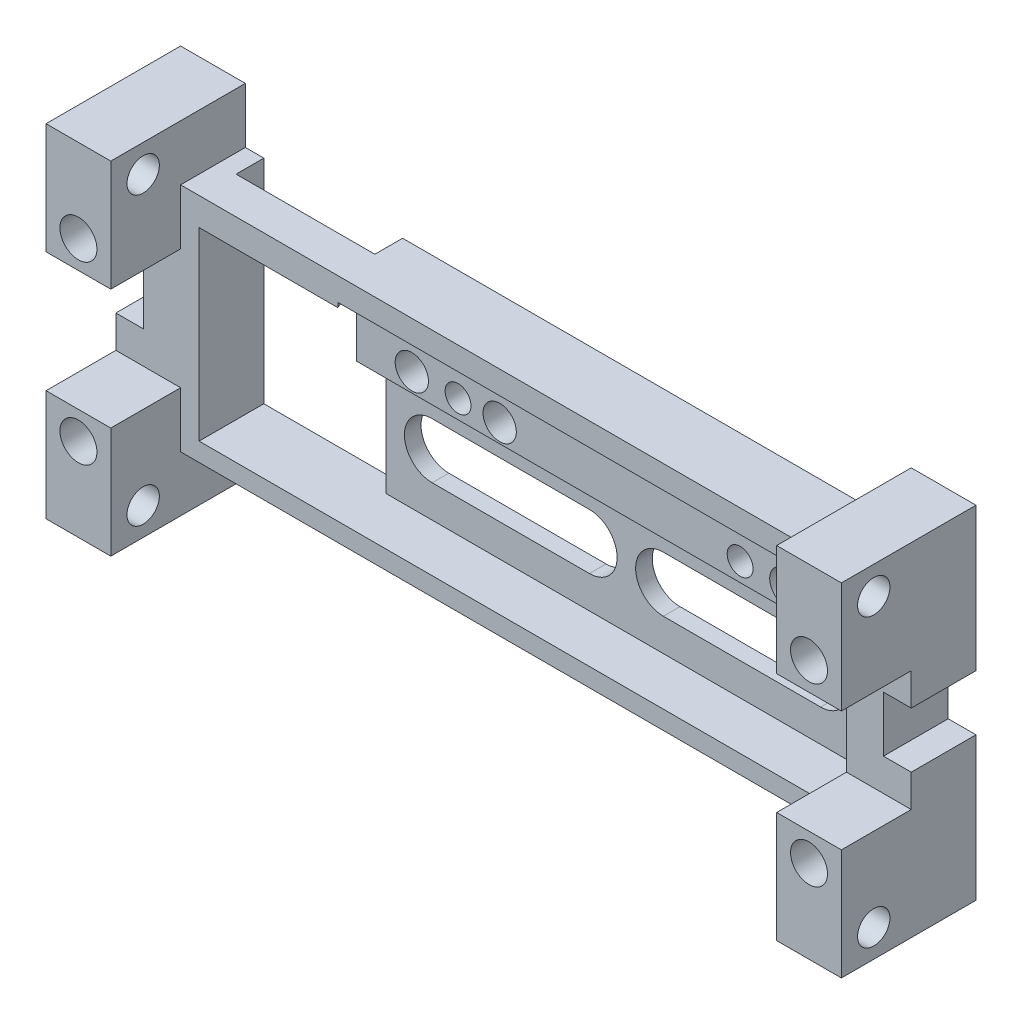
SolidWorks part; units mm, degrees
other "标注1"
sketch "草图15" plane through (0, -6, 0) normal (-0.9712, -0.0025, -0.2382) x (-0.2378, 0.0659, 0.9691)
other "标注2"
sketch "草图16" plane through (0, 31, 0) normal (-0.9763, 0.0726, -0.2038) x (-0.196, 0.1022, 0.9753)
other "标注3"
sketch "草图18" plane through (86, -6, 14) normal (0.0371, -0.0622, 0.9974) x (0.9993, -0.0087, -0.0377)
ref_plane "前视基准面" through (0, 0, 0) normal (0, 0, 1) x (1, 0, 0)
ref_plane "上视基准面" through (0, 0, 0) normal (0, 1, 0) x (1, 0, 0)
ref_plane "右视基准面" through (0, 0, 0) normal (1, 0, 0) x (0, 0, -1)
other "Configuration Table"
sketch "草图1" plane through (0, 0, 0) normal (0, 0, 1) x (1, 0, 0)
  line L1 (0, 0) -> (86, 0)
  line L2 (0, 0) -> (0, 25)
  line L3 (0, 25) -> (86, 25)
  line L4 (86, 0) -> (86, 25)
  dimension "D1" = 86
  dimension "D2" = 25
extrude "凸台-拉伸1" add sketch "草图1" along normal blind 7
sketch "草图2" plane through (0, 0, 7) normal (0, 0, 1) x (1, 0, 0)
  line L0 (0, 25) -> (0, 0) construction
  line L1 (9, 19) -> (24, 19)
  line L2 (9, 19) -> (9, 2)
  line L3 (9, 2) -> (24, 2)
  line L4 (24, 19) -> (24, 2)
  line L5 (86, 25) -> (0, 25) construction
  dimension "D1" = 15
  dimension "D2" = 17
  dimension "D3" = 9
  dimension "D4" = 6
extrude "切除-拉伸1" cut sketch "草图2" against normal through all
sketch "草图3" plane through (0, 0, 7) normal (0, 0, 1) x (1, 0, 0)
  line L1 (24, 2) -> (79, 2)
  line L2 (24, 2) -> (24, 15)
  line L3 (24, 15) -> (79, 15)
  line L4 (79, 2) -> (79, 15)
  dimension "D1" = 55
  dimension "D2" = 13
extrude "切除-拉伸2" cut sketch "草图3" against normal blind 5.2
sketch "草图4" plane through (0, 0, 7) normal (0, 0, 1) x (1, 0, 0)
  line L0 (79, 2) -> (79, 15) construction
  line L1 (24, 15) -> (79, 15)
  line L2 (24, 15) -> (24, 22.5)
  line L3 (24, 22.5) -> (79, 22.5)
  line L4 (79, 15) -> (79, 22.5)
  dimension "D1" = 7.5
extrude "切除-拉伸3" cut sketch "草图4" against normal blind 2
chamfer "倒角1" distance 1 angle 45 1 edges at (51.5, 15, 5)
sketch "草图5" plane through (0, 0, 5) normal (0, 0, 1) x (1, 0, 0)
  line L0 (24, 19) -> (24, 16) construction
  line L1 (79, 22.5) -> (24, 22.5) construction
  circle A0 centre (30, 18) radius 1.8
  circle A1 centre (39.5, 18) radius 1.8
  circle A2 centre (70.5, 18) radius 1.8
  dimension "D4" = 3.6
  dimension "D1" = 6
  dimension "D2" = 9.5
  dimension "D3" = 31
  dimension "D5" = 4.5
extrude "切除-拉伸4" cut sketch "草图5" against normal through all
sketch "草图6" plane through (0, 0, 5) normal (0, 0, 1) x (1, 0, 0)
  line L0 (79, 22.5) -> (24, 22.5) construction
  line L1 (24, 19) -> (24, 16) construction
  circle A0 centre (35, 18) radius 1.4
  circle A1 centre (65.5, 18) radius 1.4
  dimension "D3" = 2.8
  dimension "D1" = 4.5
  dimension "D2" = 11
  dimension "D4" = 41.5
extrude "切除-拉伸5" cut sketch "草图6" against normal through all
sketch "草图7" plane through (0, 0, 1.8) normal (0, 0, 1) x (1, 0, 0)
  line L0 (29, 8.5) -> (46, 8.5) construction
  line L1 (29, 11.5) -> (46, 11.5)
  line L2 (29, 5.5) -> (46, 5.5)
  line L3 (54, 8.5) -> (71, 8.5) construction
  line L4 (54, 11.5) -> (71, 11.5)
  line L5 (54, 5.5) -> (71, 5.5)
  line L6 (24, 15) -> (24, 2) construction
  arc A0 (29, 11.5) -> (29, 5.5) centre (29, 8.5) ccw
  arc A1 (46, 5.5) -> (46, 11.5) centre (46, 8.5) ccw
  arc A2 (54, 11.5) -> (54, 5.5) centre (54, 8.5) ccw
  arc A3 (71, 5.5) -> (71, 11.5) centre (71, 8.5) ccw
  point P2 (37.5, 8.5)
  point P7 (62.5, 8.5)
  point P16 (24, 8.5)
  dimension "D2" = 3
  dimension "D3" = 3
  dimension "D1" = 8
  dimension "D4" = 5
  dimension "D5" = 17
  dimension "D6" = 17
extrude "切除-拉伸6" cut sketch "草图7" against normal through all
sketch "草图8" plane through (0, 0, 7) normal (0, 0, 1) x (1, 0, 0)
  line L0 (86, 0) -> (86, 25) construction
  line L1 (0, 25) -> (7, 25)
  line L2 (0, 25) -> (0, 19)
  line L3 (0, 19) -> (7, 19)
  line L4 (7, 25) -> (7, 19)
  line L5 (79, 6) -> (86, 6)
  line L6 (79, 6) -> (79, 0)
  line L7 (79, 0) -> (86, 0)
  line L8 (86, 6) -> (86, 0)
  line L9 (0, 0) -> (86, 0) construction
  line L10 (86, 25) -> (0, 25) construction
  line L11 (0, 25) -> (0, 0) construction
  line L13 (0, 0) -> (7, 0)
  line L14 (0, 0) -> (0, 6)
  line L15 (0, 6) -> (7, 6)
  line L16 (7, 0) -> (7, 6)
  line L17 (86, 25) -> (79, 25)
  line L18 (86, 25) -> (86, 19)
  line L19 (86, 19) -> (79, 19)
  line L20 (79, 25) -> (79, 19)
  dimension "D1" = 7
  dimension "D2" = 6
  dimension "D3" = 7
  dimension "D4" = 6
  dimension "D5" = 7
  dimension "D6" = 6
  dimension "D7" = 7
  dimension "D8" = 6
extrude "凸台-拉伸2" add sketch "草图8" along normal blind 7.55
sketch "草图9" plane through (0, 0, 14.55) normal (0, 0, 1) x (1, 0, 0)
  line L0 (7, 25) -> (0, 25) construction
  line L1 (7, 19) -> (7, 25) construction
  line L2 (86, 6) -> (79, 6) construction
  line L3 (86, 0) -> (86, 6) construction
  circle A0 centre (3.5, 22) radius 2
  circle A1 centre (82.5, 3) radius 2
  circle A2 centre (82.5, 22) radius 2
  circle A3 centre (3.5, 3) radius 2
  point P7 (3.5, 25)
  point P10 (7, 22)
  point P13 (82.5, 6)
  point P16 (86, 3)
  dimension "D1" = 4
extrude "切除-拉伸7" cut sketch "草图9" against normal through all
sketch "草图10" plane through (0, 0, 0) normal (-1, 0, 0) x (0, 0, 1)
  line L0 (0, 25) -> (0, 31)
  line L1 (0, 31) -> (14.55, 31)
  line L2 (14.55, 31) -> (14.55, 25)
  line L3 (14.55, 25) -> (0, 25) construction
  line L4 (0, 25) -> (14.55, 25)
  line L5 (0, 0) -> (14.55, 0)
  line L6 (14.55, 0) -> (14.55, -6)
  line L7 (14.55, -6) -> (0, -6)
  line L8 (0, -6) -> (0, 0)
  line L9 (14.55, 25) -> (14.55, 19) construction
  line L10 (14.55, 6) -> (14.55, 0) construction
  line L11 (0, 25) -> (0, 0) construction
  circle A0 centre (11.05, 28) radius 1.75
  circle A1 centre (11.05, -3) radius 1.75
  dimension "D4" = 3.5
  dimension "D1" = 6
  dimension "D3" = 3
  dimension "D6" = 6
  dimension "D7" = 3
  dimension "D9" = 3.5
extrude "凸台-拉伸3" add sketch "草图10" against normal blind 7
sketch "草图12" plane through (86, 0, 0) normal (1, 0, 0) x (0, 0, -1)
  line L34 (-14.55, 25) -> (-14.55, 31)
  line L35 (-14.55, 19) -> (-14.55, 31) construction
  line L36 (-14.55, 31) -> (0, 31)
  line L37 (0, 31) -> (0, 25)
  line L38 (0, 25) -> (-14.55, 25)
  line L39 (-14.55, 0) -> (0, 0)
  line L40 (0, 0) -> (0, -6)
  line L41 (0, -6) -> (-14.55, -6)
  line L42 (-14.55, -6) -> (-14.55, 0)
  circle A16 centre (-11.05, 28) radius 1.75
  circle A17 centre (-11.05, -3) radius 1.75
  circle A18 centre (-11.05, 28) radius 1.75 construction
  circle A19 centre (-11.05, -3) radius 1.75 construction
extrude "凸台-拉伸5" add sketch "草图12" against normal blind 7
sketch "草图13" plane through (0, 0, 0) normal (-1, 0, 0) x (0, 0, 1)
  line L5 (0, 31) -> (0, -6) construction
  line L6 (0, 9.5) -> (7, 9.5)
  line L7 (0, 9.5) -> (0, 15.5)
  line L8 (0, 15.5) -> (7, 15.5)
  line L9 (7, 9.5) -> (7, 15.5)
  line L10 (7, 19) -> (7, 6) construction
  point P9 (7, 12.5)
  point P10 (7, 12.5)
  dimension "D1" = 6
extrude "切除-拉伸8" cut sketch "草图13" against normal blind 3
sketch "草图14" plane through (86, 0, 0) normal (1, 0, 0) x (0, 0, -1)
  line L7 (-7, 6) -> (-7, 19) construction
  line L8 (-7, 15.5) -> (0, 15.5)
  line L9 (-7, 15.5) -> (-7, 9.5)
  line L10 (-7, 9.5) -> (0, 9.5)
  line L11 (0, 15.5) -> (0, 9.5)
  line L12 (0, -6) -> (0, 31) construction
  point P6 (-7, 12.5)
  point P7 (0, 12.5)
  dimension "D1" = 6
extrude "切除-拉伸9" cut sketch "草图14" against normal blind 3
ref_plane "基准面1" through (24, 0, 0) normal (-1, 0, 0) x (0, 0, 1)
sketch "草图20" plane through (24, 0, 0) normal (-1, 0, 0) x (0, 0, 1)
  line L3 (0, 19) -> (7, 19)
  line L4 (7, 19) -> (7, 22)
  line L5 (7, 22) -> (3, 25)
  line L6 (3, 25) -> (0, 25)
  line L7 (0, 25) -> (0, 19)
  line L8 (0, 19) -> (5, 19) construction
  line L9 (0, 2) -> (0, 19) construction
  line L10 (7, 22.5) -> (7, 19) construction
  dimension "D1" = 3
  dimension "D2" = 3
  dimension "D3" = 6
extrude "切除-拉伸10" cut sketch "草图20" along normal up to surface (15 mm away) up to face at (9, 10.5, 3.5)
